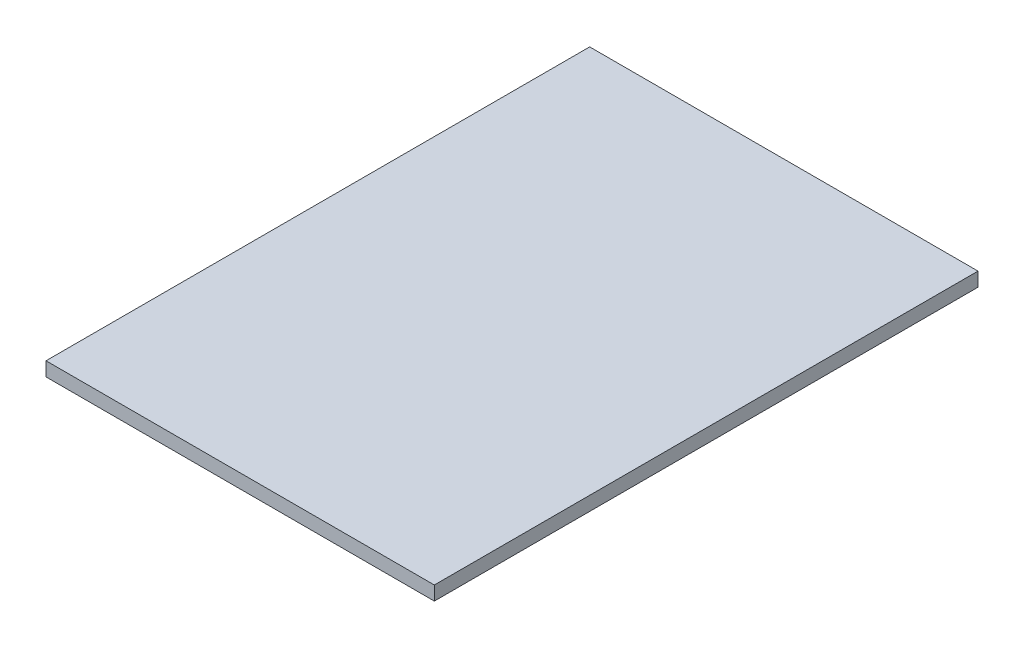
SolidWorks part; units mm, degrees
ref_plane "Front Plane" through (0, 0, 0) normal (0, 0, 1) x (1, 0, 0)
ref_plane "Top Plane" through (0, 0, 0) normal (0, 1, 0) x (1, 0, 0)
ref_plane "Right Plane" through (0, 0, 0) normal (1, 0, 0) x (0, 0, -1)
sketch "Esquisse1" plane through (0, 0, 0) normal (0, 1, 0) x (1, 0, 0)
  line L1 (-250, 350) -> (250, 350)
  line L2 (-250, 350) -> (-250, -350)
  line L3 (-250, -350) -> (250, -350)
  line L4 (250, 350) -> (250, -350)
  line L5 (-250, 350) -> (250, -350) construction
  line L6 (-250, -350) -> (250, 350) construction
  point P0 (0, 0)
extrude "Boss.-Extru.1" add sketch "Esquisse1" along normal blind 18
